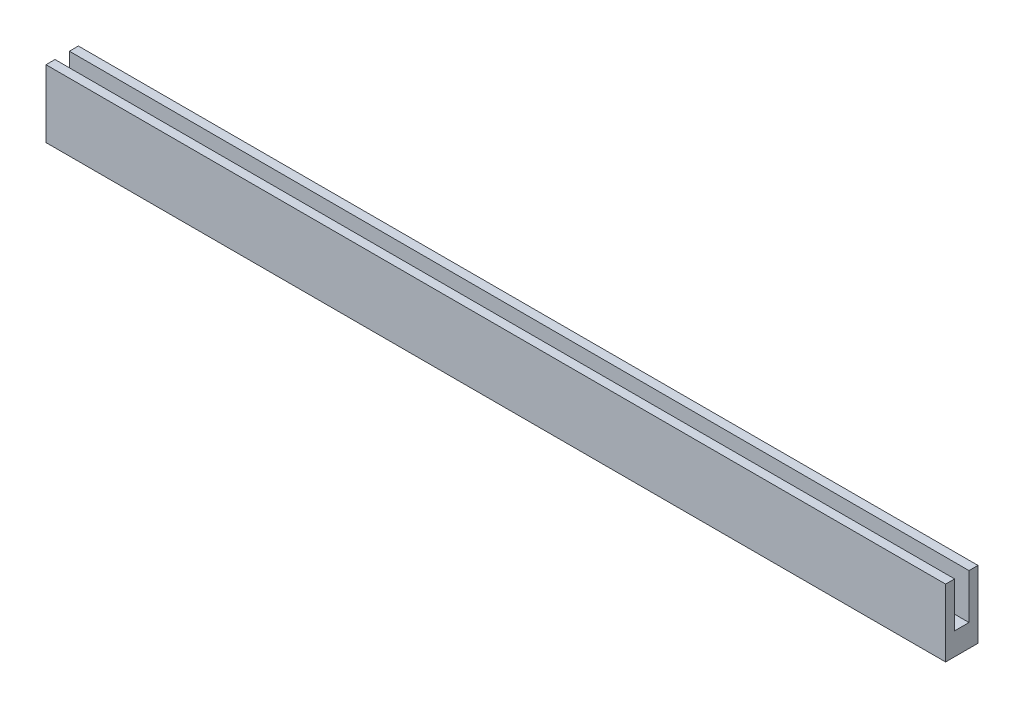
SolidWorks part; units mm, degrees
ref_plane "Front Plane" through (0, 0, 0) normal (0, 0, 1) x (1, 0, 0)
ref_plane "Top Plane" through (0, 0, 0) normal (0, 1, 0) x (1, 0, 0)
ref_plane "Right Plane" through (0, 0, 0) normal (1, 0, 0) x (0, 0, -1)
sketch "Sketch1" plane through (0, 0, 0) normal (1, 0, 0) x (0, 0, -1)
  line L0 (0, 9.6913) -> (0, 0)
  line L1 (0, 0) -> (-7.2, 0)
  line L2 (-7.2, 0) -> (-7.2, 15)
  line L3 (-7.2, 15) -> (-5.2, 15)
  line L4 (-5.2, 15) -> (-5.2, 5)
  line L5 (-5.2, 5) -> (-2, 5)
  line L6 (-2, 5) -> (-2, -3.0475)
  line L7 (-2, 15) -> (0, 15)
  line L8 (0, 15) -> (0, 9.6913)
  line L9 (-2, -3.0475) -> (-2, 15)
  dimension "D1" = 15
  dimension "D2" = 3.2
  dimension "D3" = 2
  dimension "D4" = 2
  dimension "D5" = 10
extrude "Boss-Extrude2" add sketch "Sketch1" along normal blind 200 contours L6 L5 L4 L3 L2 L1 | L9 L6 L1 L0 L8 L7
